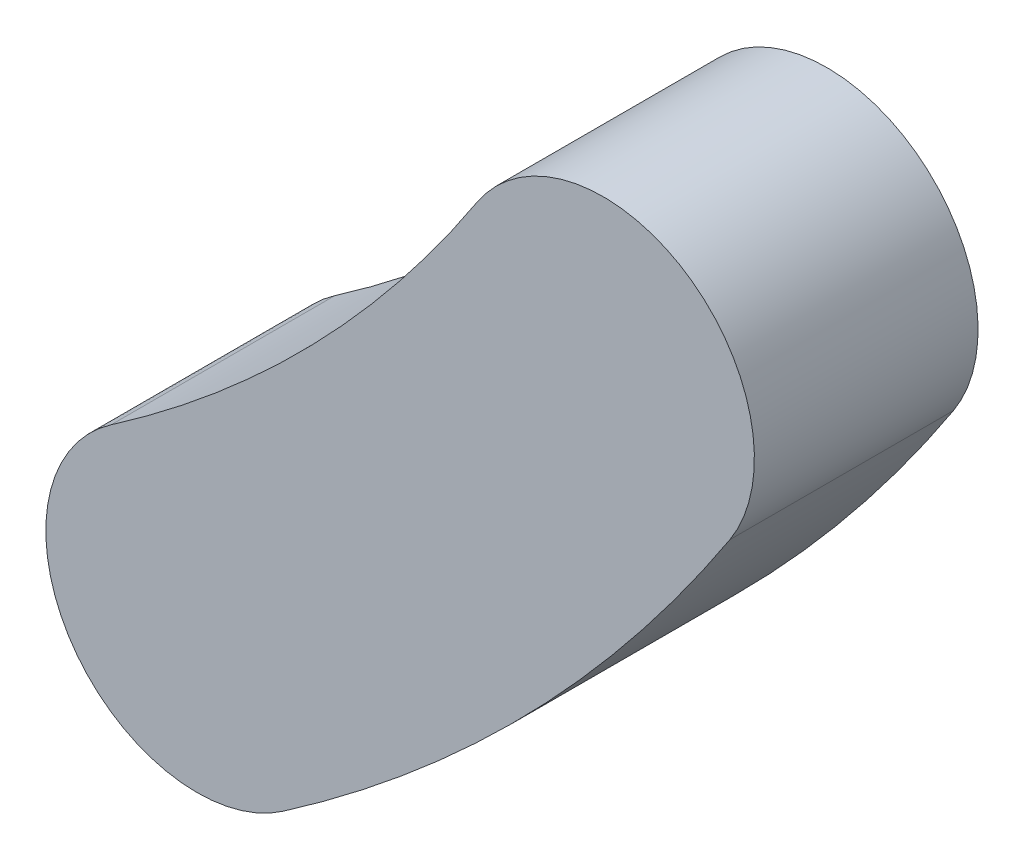
SolidWorks part; units mm, degrees
ref_plane "Front Plane" through (0, 0, 0) normal (0, 0, 1) x (1, 0, 0)
ref_plane "Top Plane" through (0, 0, 0) normal (0, 1, 0) x (1, 0, 0)
ref_plane "Right Plane" through (0, 0, 0) normal (1, 0, 0) x (0, 0, -1)
sketch "Sketch1" plane through (70, 0, 0) normal (0, 0, 1) x (1, 0, 0)
  arc A0 (26.5591, 4.4309) -> (32.0065, 10.0217) centre (15.1068, 21.0389) ccw construction
  arc A1 (27.7103, 2.7614) -> (33.7053, 8.9142) centre (15.1068, 21.0389) ccw
  arc A2 (25.4079, 6.1003) -> (30.3078, 11.1291) centre (15.1068, 21.0389) ccw
  arc A3 (25.4079, 6.1003) -> (27.7103, 2.7614) centre (26.5591, 4.4309) ccw
  arc A4 (33.7053, 8.9142) -> (30.3078, 11.1291) centre (32.0065, 10.0217) ccw
  point P3 (29.5558, 6.9603)
  point P8 (27.0269, 15.8725)
  point P9 (38.1586, 9.477)
  point P10 (14.8444, 21.5765)
  point P11 (26.6453, 4.4146)
  point P12 (31.8531, 10.4113)
  point P13 (31.0444, 10.2774)
  point P14 (26.8212, 4.5147)
  point P15 (0, 0)
  point P16 (25.2307, 4.0681)
  point P17 (23.9553, 5.1952)
  point P18 (31.3113, 10.9791)
  point P19 (26.7435, 1.8435)
  point P20 (31.6375, 10.3266)
  point P21 (30.2221, 7.5753)
  point P22 (30.8884, 8.3954)
  point P23 (0, 0)
  point P24 (30.3246, 7.5241)
  point P25 (0, 0)
  point P26 (29.5558, 6.9603)
extrude "Boss-Extrude1" add sketch "Sketch1" along normal blind 3
